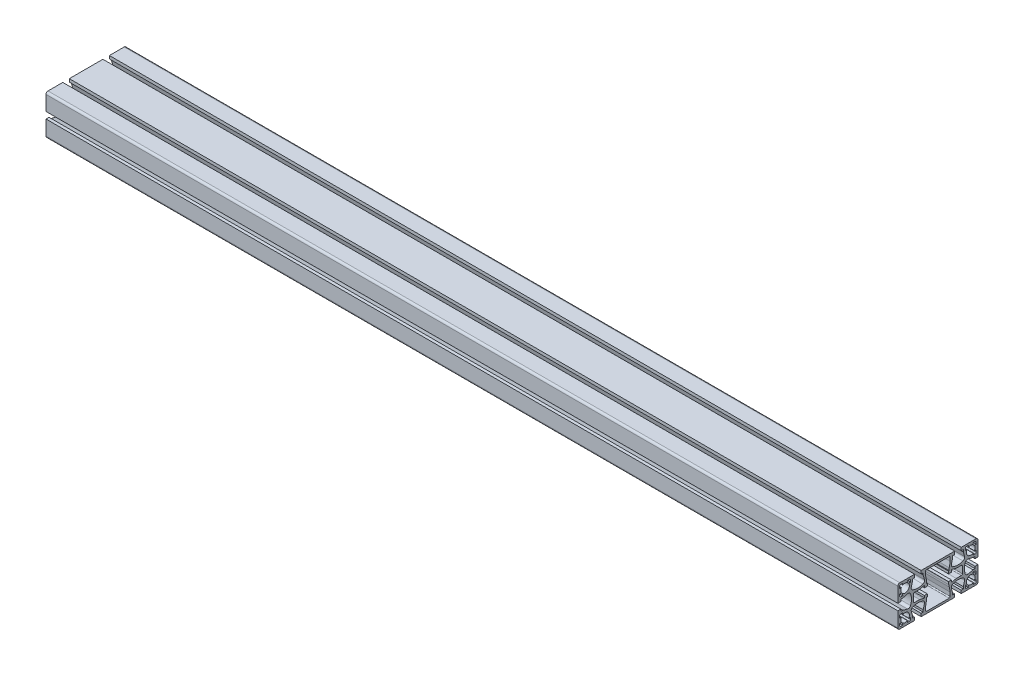
SolidWorks part; units mm, degrees
material "1060-H16"
ref_plane "前视基准面" through (0, 0, 0) normal (0, 0, 1) x (1, 0, 0)
ref_plane "上视基准面" through (0, 0, 0) normal (0, 1, 0) x (1, 0, 0)
ref_plane "右视基准面" through (0, 0, 0) normal (1, 0, 0) x (0, 0, -1)
sketch "草图1" plane through (0, 0, 0) normal (0, 0, 1) x (1, 0, 0)
  line L0 (-87.1056, 0) -> (87.1056, 0) construction
  line L1 (0, 87.1056) -> (0, -87.1056) construction
  line L2 (-425, 0) -> (425, 0)
  dimension "D1" = 850
other "结构构件1"
ref_plane "基准面1" through (-425, 0, 0) normal (1, 0, 0) x (0, 1, 0)
sketch "Sketch11" plane through (-425, 0, 0) normal (1, 0, 0) x (0, 1, 0)
  line L0 (6.5579, -30.3052) -> (5.3, -34.9997)
  line L1 (5.3, -34.9997) -> (5.3, -37)
  line L2 (5.3, -37) -> (3.25, -37)
  line L3 (3.25, -37) -> (3.25, -40)
  line L4 (13.3, 12.3) -> (17, 12.3)
  line L5 (8.3, 11.3) -> (13.3, 12.3)
  line L6 (5.8, 11.3) -> (8.3, 11.3)
  line L7 (5.8, 10.5) -> (5.8, 11.3)
  line L8 (3.25, -40) -> (18, -40)
  line L9 (20, -38) -> (20, -23.25)
  line L10 (20, -23.25) -> (17, -23.25)
  line L11 (17, -23.25) -> (17, -25.3)
  line L12 (17, -25.3) -> (14.9997, -25.3)
  line L13 (14.9997, -25.3) -> (10.3052, -26.5579)
  line L14 (10.3052, -13.4421) -> (14.9997, -14.7)
  line L15 (14.9997, -14.7) -> (17, -14.7)
  line L16 (17, -14.7) -> (17, -16.75)
  line L17 (17, -16.75) -> (20, -16.75)
  line L18 (20, -16.75) -> (20, 16.75)
  line L19 (18.1364, -37.1364) -> (18.1364, -35.308)
  line L20 (18.1364, -35.308) -> (17.6997, -34.8713)
  line L21 (17.6997, -34.8713) -> (16.9926, -35.5784)
  line L22 (16.9926, -35.5784) -> (16.4143, -35.0001)
  line L23 (16.4143, -30.4999) -> (16.9926, -29.9216)
  line L24 (16.9926, -29.9216) -> (17.6997, -30.6287)
  line L25 (17.6997, -30.6287) -> (18.1364, -30.192)
  line L26 (18.1364, -30.192) -> (18.1364, -28.3636)
  line L27 (17.1364, -27.3636) -> (15.308, -27.3636)
  line L28 (15.308, -27.3636) -> (14.8713, -27.8003)
  line L29 (14.8713, -27.8003) -> (15.5784, -28.5074)
  line L30 (15.5784, -28.5074) -> (15.0001, -29.0857)
  line L31 (9.0857, -35.0001) -> (8.5074, -35.5784)
  line L32 (8.5074, -35.5784) -> (7.8003, -34.8713)
  line L33 (7.8003, -34.8713) -> (7.3636, -35.308)
  line L34 (7.3636, -35.308) -> (7.3636, -37.1364)
  line L35 (8.3636, -38.1364) -> (10.192, -38.1364)
  line L36 (10.192, -38.1364) -> (10.6287, -37.6997)
  line L37 (10.6287, -37.6997) -> (9.9216, -36.9926)
  line L38 (9.9216, -36.9926) -> (10.4999, -36.4143)
  line L39 (15.0001, -36.4143) -> (15.5784, -36.9926)
  line L40 (15.5784, -36.9926) -> (14.8713, -37.6997)
  line L41 (14.8713, -37.6997) -> (15.308, -38.1364)
  line L42 (15.308, -38.1364) -> (17.1364, -38.1364)
  line L43 (-3.4, -24.4) -> (3.4, -24.4)
  line L44 (4.4, -23.4) -> (4.4, -18.2864)
  line L45 (4.4, -18.2864) -> (5.35, -14.5)
  line L46 (5.35, -14.5) -> (5.35, -13.5)
  line L47 (5.35, -13.5) -> (3.3, -13.5)
  line L48 (3.3, -13.5) -> (3.3, -10.6)
  line L49 (3.4, -10.5) -> (5.8, -10.5)
  line L50 (5.8, -10.5) -> (5.8, -11.3)
  line L51 (5.8, -11.3) -> (8.3, -11.3)
  line L52 (8.3, -11.3) -> (13.3, -12.3)
  line L53 (13.3, -12.3) -> (17, -12.3)
  line L54 (18, -11.3) -> (18, 11.3)
  line L55 (20, 0) -> (-18, 0) construction
  line L56 (0, 0) -> (0, -60.5925) construction
  line L57 (3.4, 10.5) -> (5.8, 10.5)
  line L58 (3.3, 13.5) -> (3.3, 10.6)
  line L59 (5.35, 13.5) -> (3.3, 13.5)
  line L60 (5.35, 14.5) -> (5.35, 13.5)
  line L61 (4.4, 18.2864) -> (5.35, 14.5)
  line L62 (4.4, 23.4) -> (4.4, 18.2864)
  line L63 (-3.4, 24.4) -> (3.4, 24.4)
  line L64 (15.308, 38.1364) -> (17.1364, 38.1364)
  line L65 (14.8713, 37.6997) -> (15.308, 38.1364)
  line L66 (15.5784, 36.9926) -> (14.8713, 37.6997)
  line L67 (15.0001, 36.4143) -> (15.5784, 36.9926)
  line L68 (9.9216, 36.9926) -> (10.4999, 36.4143)
  line L69 (10.6287, 37.6997) -> (9.9216, 36.9926)
  line L70 (10.192, 38.1364) -> (10.6287, 37.6997)
  line L71 (8.3636, 38.1364) -> (10.192, 38.1364)
  line L72 (7.3636, 35.308) -> (7.3636, 37.1364)
  line L73 (7.8003, 34.8713) -> (7.3636, 35.308)
  line L74 (8.5074, 35.5784) -> (7.8003, 34.8713)
  line L75 (9.0857, 35.0001) -> (8.5074, 35.5784)
  line L76 (15.5784, 28.5074) -> (15.0001, 29.0857)
  line L77 (14.8713, 27.8003) -> (15.5784, 28.5074)
  line L78 (15.308, 27.3636) -> (14.8713, 27.8003)
  line L79 (17.1364, 27.3636) -> (15.308, 27.3636)
  line L80 (18.1364, 30.192) -> (18.1364, 28.3636)
  line L81 (17.6997, 30.6287) -> (18.1364, 30.192)
  line L82 (16.9926, 29.9216) -> (17.6997, 30.6287)
  line L83 (16.4143, 30.4999) -> (16.9926, 29.9216)
  line L84 (16.9926, 35.5784) -> (16.4143, 35.0001)
  line L85 (17.6997, 34.8713) -> (16.9926, 35.5784)
  line L86 (18.1364, 35.308) -> (17.6997, 34.8713)
  line L87 (18.1364, 37.1364) -> (18.1364, 35.308)
  line L88 (17, 16.75) -> (20, 16.75)
  line L89 (17, 14.7) -> (17, 16.75)
  line L90 (14.9997, 14.7) -> (17, 14.7)
  line L91 (10.3052, 13.4421) -> (14.9997, 14.7)
  line L92 (14.9997, 25.3) -> (10.3052, 26.5579)
  line L93 (17, 25.3) -> (14.9997, 25.3)
  line L94 (17, 23.25) -> (17, 25.3)
  line L95 (20, 23.25) -> (17, 23.25)
  line L96 (20, 38) -> (20, 23.25)
  line L97 (3.25, 40) -> (18, 40)
  line L98 (3.25, 37) -> (3.25, 40)
  line L99 (5.3, 37) -> (3.25, 37)
  line L100 (5.3, 34.9997) -> (5.3, 37)
  line L101 (6.5579, 30.3052) -> (5.3, 34.9997)
  line L102 (-6.5579, 30.3052) -> (-5.3, 34.9997)
  line L103 (-5.3, 34.9997) -> (-5.3, 37)
  line L104 (-5.3, 37) -> (-3.25, 37)
  line L105 (-3.25, 37) -> (-3.25, 40)
  line L106 (-3.25, 40) -> (-18, 40)
  line L107 (-20, 38) -> (-20, 23.25)
  line L108 (-20, 23.25) -> (-17, 23.25)
  line L109 (-17, 23.25) -> (-17, 25.3)
  line L110 (-17, 25.3) -> (-14.9997, 25.3)
  line L111 (-14.9997, 25.3) -> (-10.3052, 26.5579)
  line L112 (-10.3052, 13.4421) -> (-14.9997, 14.7)
  line L113 (-14.9997, 14.7) -> (-17, 14.7)
  line L114 (-17, 14.7) -> (-17, 16.75)
  line L115 (-17, 16.75) -> (-20, 16.75)
  line L116 (-18.1364, 37.1364) -> (-18.1364, 35.308)
  line L117 (-18.1364, 35.308) -> (-17.6997, 34.8713)
  line L118 (-17.6997, 34.8713) -> (-16.9926, 35.5784)
  line L119 (-16.9926, 35.5784) -> (-16.4143, 35.0001)
  line L120 (-16.4143, 30.4999) -> (-16.9926, 29.9216)
  line L121 (-16.9926, 29.9216) -> (-17.6997, 30.6287)
  line L122 (-17.6997, 30.6287) -> (-18.1364, 30.192)
  line L123 (-18.1364, 30.192) -> (-18.1364, 28.3636)
  line L124 (-17.1364, 27.3636) -> (-15.308, 27.3636)
  line L125 (-15.308, 27.3636) -> (-14.8713, 27.8003)
  line L126 (-14.8713, 27.8003) -> (-15.5784, 28.5074)
  line L127 (-15.5784, 28.5074) -> (-15.0001, 29.0857)
  line L128 (-9.0857, 35.0001) -> (-8.5074, 35.5784)
  line L129 (-8.5074, 35.5784) -> (-7.8003, 34.8713)
  line L130 (-7.8003, 34.8713) -> (-7.3636, 35.308)
  line L131 (-7.3636, 35.308) -> (-7.3636, 37.1364)
  line L132 (-8.3636, 38.1364) -> (-10.192, 38.1364)
  line L133 (-10.192, 38.1364) -> (-10.6287, 37.6997)
  line L134 (-10.6287, 37.6997) -> (-9.9216, 36.9926)
  line L135 (-9.9216, 36.9926) -> (-10.4999, 36.4143)
  line L136 (-15.0001, 36.4143) -> (-15.5784, 36.9926)
  line L137 (-15.5784, 36.9926) -> (-14.8713, 37.6997)
  line L138 (-14.8713, 37.6997) -> (-15.308, 38.1364)
  line L139 (-15.308, 38.1364) -> (-17.1364, 38.1364)
  line L140 (-4.4, 23.4) -> (-4.4, 18.2864)
  line L141 (-4.4, 18.2864) -> (-5.35, 14.5)
  line L142 (-5.35, 14.5) -> (-5.35, 13.5)
  line L143 (-5.35, 13.5) -> (-3.3, 13.5)
  line L144 (-3.3, 13.5) -> (-3.3, 10.6)
  line L145 (-3.4, 10.5) -> (-5.8, 10.5)
  line L146 (-18, -11.3) -> (-18, 11.3)
  line L147 (-13.3, -12.3) -> (-17, -12.3)
  line L148 (-8.3, -11.3) -> (-13.3, -12.3)
  line L149 (-5.8, -11.3) -> (-8.3, -11.3)
  line L150 (-5.8, -10.5) -> (-5.8, -11.3)
  line L151 (-3.4, -10.5) -> (-5.8, -10.5)
  line L152 (-3.3, -13.5) -> (-3.3, -10.6)
  line L153 (-5.35, -13.5) -> (-3.3, -13.5)
  line L154 (-5.35, -14.5) -> (-5.35, -13.5)
  line L155 (-4.4, -18.2864) -> (-5.35, -14.5)
  line L156 (-4.4, -23.4) -> (-4.4, -18.2864)
  line L157 (-15.308, -38.1364) -> (-17.1364, -38.1364)
  line L158 (-14.8713, -37.6997) -> (-15.308, -38.1364)
  line L159 (-15.5784, -36.9926) -> (-14.8713, -37.6997)
  line L160 (-15.0001, -36.4143) -> (-15.5784, -36.9926)
  line L161 (-9.9216, -36.9926) -> (-10.4999, -36.4143)
  line L162 (-10.6287, -37.6997) -> (-9.9216, -36.9926)
  line L163 (-10.192, -38.1364) -> (-10.6287, -37.6997)
  line L164 (-8.3636, -38.1364) -> (-10.192, -38.1364)
  line L165 (-7.3636, -35.308) -> (-7.3636, -37.1364)
  line L166 (-7.8003, -34.8713) -> (-7.3636, -35.308)
  line L167 (-8.5074, -35.5784) -> (-7.8003, -34.8713)
  line L168 (-9.0857, -35.0001) -> (-8.5074, -35.5784)
  line L169 (-15.5784, -28.5074) -> (-15.0001, -29.0857)
  line L170 (-14.8713, -27.8003) -> (-15.5784, -28.5074)
  line L171 (-15.308, -27.3636) -> (-14.8713, -27.8003)
  line L172 (-17.1364, -27.3636) -> (-15.308, -27.3636)
  line L173 (-18.1364, -30.192) -> (-18.1364, -28.3636)
  line L174 (-17.6997, -30.6287) -> (-18.1364, -30.192)
  line L175 (-16.9926, -29.9216) -> (-17.6997, -30.6287)
  line L176 (-16.4143, -30.4999) -> (-16.9926, -29.9216)
  line L177 (-16.9926, -35.5784) -> (-16.4143, -35.0001)
  line L178 (-17.6997, -34.8713) -> (-16.9926, -35.5784)
  line L179 (-18.1364, -35.308) -> (-17.6997, -34.8713)
  line L180 (-18.1364, -37.1364) -> (-18.1364, -35.308)
  line L181 (-20, -16.75) -> (-20, 16.75)
  line L182 (-17, -16.75) -> (-20, -16.75)
  line L183 (-17, -14.7) -> (-17, -16.75)
  line L184 (-14.9997, -14.7) -> (-17, -14.7)
  line L185 (-10.3052, -13.4421) -> (-14.9997, -14.7)
  line L186 (-14.9997, -25.3) -> (-10.3052, -26.5579)
  line L187 (-17, -25.3) -> (-14.9997, -25.3)
  line L188 (-17, -23.25) -> (-17, -25.3)
  line L189 (-20, -23.25) -> (-17, -23.25)
  line L190 (-20, -38) -> (-20, -23.25)
  line L191 (-3.25, -40) -> (-18, -40)
  line L192 (-5.8, 10.5) -> (-5.8, 11.3)
  line L193 (-5.8, 11.3) -> (-8.3, 11.3)
  line L194 (-8.3, 11.3) -> (-13.3, 12.3)
  line L195 (-13.3, 12.3) -> (-17, 12.3)
  line L196 (-3.25, -37) -> (-3.25, -40)
  line L197 (-5.3, -37) -> (-3.25, -37)
  line L198 (-5.3, -34.9997) -> (-5.3, -37)
  line L199 (-6.5579, -30.3052) -> (-5.3, -34.9997)
  line L200 (-3.25, 40) -> (3.25, 40) construction
  line L201 (-3.25, -40) -> (3.25, -40) construction
  arc A0 (17, 12.3) -> (18, 11.3) centre (17, 11.3) cw
  arc A1 (3.4, 10.5) -> (3.3, 10.6) centre (3.4, 10.6) cw
  arc A2 (3.4, 24.4) -> (4.4, 23.4) centre (3.4, 23.4) cw
  arc A3 (17.1364, 38.1364) -> (18.1364, 37.1364) centre (17.1364, 37.1364) cw
  arc A4 (5.0284, -27.3201) -> (-5.0284, -27.3201) centre (0, -40.6) ccw
  arc A5 (6.5579, -30.3052) -> (5.0284, -27.3201) centre (4.1431, -29.6581) ccw
  arc A6 (18, -40) -> (20, -38) centre (18, -38) ccw
  arc A7 (7.3201, -25.0284) -> (10.3052, -26.5579) centre (9.6581, -24.1431) ccw
  arc A8 (7.3201, -14.9716) -> (7.3201, -25.0284) centre (20.6, -20) ccw
  arc A9 (10.3052, -13.4421) -> (7.3201, -14.9716) centre (9.6581, -15.8569) ccw
  arc A10 (16.4143, -35.0001) -> (16.4143, -30.4999) centre (12.75, -32.75) ccw
  arc A11 (18.1364, -28.3636) -> (17.1364, -27.3636) centre (17.1364, -28.3636) ccw
  arc A12 (15.0001, -29.0857) -> (9.0857, -35.0001) centre (12.75, -32.75) ccw
  arc A13 (7.3636, -37.1364) -> (8.3636, -38.1364) centre (8.3636, -37.1364) ccw
  arc A14 (10.4999, -36.4143) -> (15.0001, -36.4143) centre (12.75, -32.75) ccw
  arc A15 (17.1364, -38.1364) -> (18.1364, -37.1364) centre (17.1364, -37.1364) ccw
  arc A16 (3.4, -24.4) -> (4.4, -23.4) centre (3.4, -23.4) ccw
  arc A17 (3.4, -10.5) -> (3.3, -10.6) centre (3.4, -10.6) ccw
  arc A18 (17, -12.3) -> (18, -11.3) centre (17, -11.3) ccw
  arc A19 (10.4999, 36.4143) -> (15.0001, 36.4143) centre (12.75, 32.75) cw
  arc A20 (7.3636, 37.1364) -> (8.3636, 38.1364) centre (8.3636, 37.1364) cw
  arc A21 (15.0001, 29.0857) -> (9.0857, 35.0001) centre (12.75, 32.75) cw
  arc A22 (18.1364, 28.3636) -> (17.1364, 27.3636) centre (17.1364, 28.3636) cw
  arc A23 (16.4143, 35.0001) -> (16.4143, 30.4999) centre (12.75, 32.75) cw
  arc A24 (10.3052, 13.4421) -> (7.3201, 14.9716) centre (9.6581, 15.8569) cw
  arc A25 (7.3201, 14.9716) -> (7.3201, 25.0284) centre (20.6, 20) cw
  arc A26 (7.3201, 25.0284) -> (10.3052, 26.5579) centre (9.6581, 24.1431) cw
  arc A27 (18, 40) -> (20, 38) centre (18, 38) cw
  arc A28 (6.5579, 30.3052) -> (5.0284, 27.3201) centre (4.1431, 29.6581) cw
  arc A29 (5.0284, 27.3201) -> (-5.0284, 27.3201) centre (0, 40.6) cw
  arc A30 (-6.5579, 30.3052) -> (-5.0284, 27.3201) centre (-4.1431, 29.6581) ccw
  arc A31 (-18, 40) -> (-20, 38) centre (-18, 38) ccw
  arc A32 (-7.3201, 25.0284) -> (-10.3052, 26.5579) centre (-9.6581, 24.1431) ccw
  arc A33 (-7.3201, 14.9716) -> (-7.3201, 25.0284) centre (-20.6, 20) ccw
  arc A34 (-10.3052, 13.4421) -> (-7.3201, 14.9716) centre (-9.6581, 15.8569) ccw
  arc A35 (-16.4143, 35.0001) -> (-16.4143, 30.4999) centre (-12.75, 32.75) ccw
  arc A36 (-18.1364, 28.3636) -> (-17.1364, 27.3636) centre (-17.1364, 28.3636) ccw
  arc A37 (-15.0001, 29.0857) -> (-9.0857, 35.0001) centre (-12.75, 32.75) ccw
  arc A38 (-7.3636, 37.1364) -> (-8.3636, 38.1364) centre (-8.3636, 37.1364) ccw
  arc A39 (-10.4999, 36.4143) -> (-15.0001, 36.4143) centre (-12.75, 32.75) ccw
  arc A40 (-17, -12.3) -> (-18, -11.3) centre (-17, -11.3) cw
  arc A41 (-3.4, -10.5) -> (-3.3, -10.6) centre (-3.4, -10.6) cw
  arc A42 (-3.4, -24.4) -> (-4.4, -23.4) centre (-3.4, -23.4) cw
  arc A43 (-17.1364, -38.1364) -> (-18.1364, -37.1364) centre (-17.1364, -37.1364) cw
  arc A44 (-10.4999, -36.4143) -> (-15.0001, -36.4143) centre (-12.75, -32.75) cw
  arc A45 (-7.3636, -37.1364) -> (-8.3636, -38.1364) centre (-8.3636, -37.1364) cw
  arc A46 (-15.0001, -29.0857) -> (-9.0857, -35.0001) centre (-12.75, -32.75) cw
  arc A47 (-18.1364, -28.3636) -> (-17.1364, -27.3636) centre (-17.1364, -28.3636) cw
  arc A48 (-16.4143, -35.0001) -> (-16.4143, -30.4999) centre (-12.75, -32.75) cw
  arc A49 (-10.3052, -13.4421) -> (-7.3201, -14.9716) centre (-9.6581, -15.8569) cw
  arc A50 (-7.3201, -14.9716) -> (-7.3201, -25.0284) centre (-20.6, -20) cw
  arc A51 (-7.3201, -25.0284) -> (-10.3052, -26.5579) centre (-9.6581, -24.1431) cw
  arc A52 (-18, -40) -> (-20, -38) centre (-18, -38) cw
  arc A53 (-6.5579, -30.3052) -> (-5.0284, -27.3201) centre (-4.1431, -29.6581) cw
  arc A54 (-17.1364, 38.1364) -> (-18.1364, 37.1364) centre (-17.1364, 37.1364) ccw
  arc A55 (-3.4, 24.4) -> (-4.4, 23.4) centre (-3.4, 23.4) ccw
  arc A56 (-3.4, 10.5) -> (-3.3, 10.6) centre (-3.4, 10.6) ccw
  arc A57 (-17, 12.3) -> (-18, 11.3) centre (-17, 11.3) ccw
  point P8 (0, 0)
  point P126 (18, 0)
  point P239 (-18, 0)
  point P270 (0, 24.4)
  point P283 (0, -24.4)
  point P316 (20, 0)
  point P317 (-20, 0)
  point P318 (0, -40)
  point P319 (0, 40)
  point P320 (-20, 40)
  point P321 (20, 40)
  point P322 (-20, -40)
  point P323 (20, -40)
  point P324 (0, 0)
hole_wizard "M6 凹头盖螺钉的柱形沉头孔1" positions "草图3" profile "草图2" counterbore size "M6" standard "Ansi Metric"
sketch "草图3" plane through (0, -20, 0) normal (0, -1, 0) x (1, 0, 0)
  line L1 (0, -38) -> (0, 38) construction
  line L2 (425, -38) -> (-425, -38) construction
  line L3 (425, 38) -> (-425, 38) construction
  line L5 (0, 0) -> (96.12, 0) construction
  point P0 (80, -20)
  point P1 (0, -20)
  point P3 (-80, -20)
  point P9 (0, 20)
  point P11 (80, 20)
  point P15 (-80, 20)
  dimension "D1" = 40
  dimension "D2" = 160
sketch "草图2" plane through (80, -20, -20) normal (1, 0, 0) x (0, 0, -1)
  line L0 (0, 0) -> (0, 40)
  line L1 (0, 40) -> (3.25, 40)
  line L3 (3.25, 40) -> (3.25, 6)
  line L4 (3.25, 6) -> (5.5, 6)
  line L5 (5.5, 6) -> (5.5, 0)
  line L7 (5.5, 0) -> (0, 0)
  line L11 (0, -6.35) -> (0, 107.95) construction
  dimension "通孔孔直径" = 6.5
  dimension "通孔孔深度" = 40
  dimension "柱形沉头孔直径" = 11
  dimension "柱形沉头孔深度" = 6
